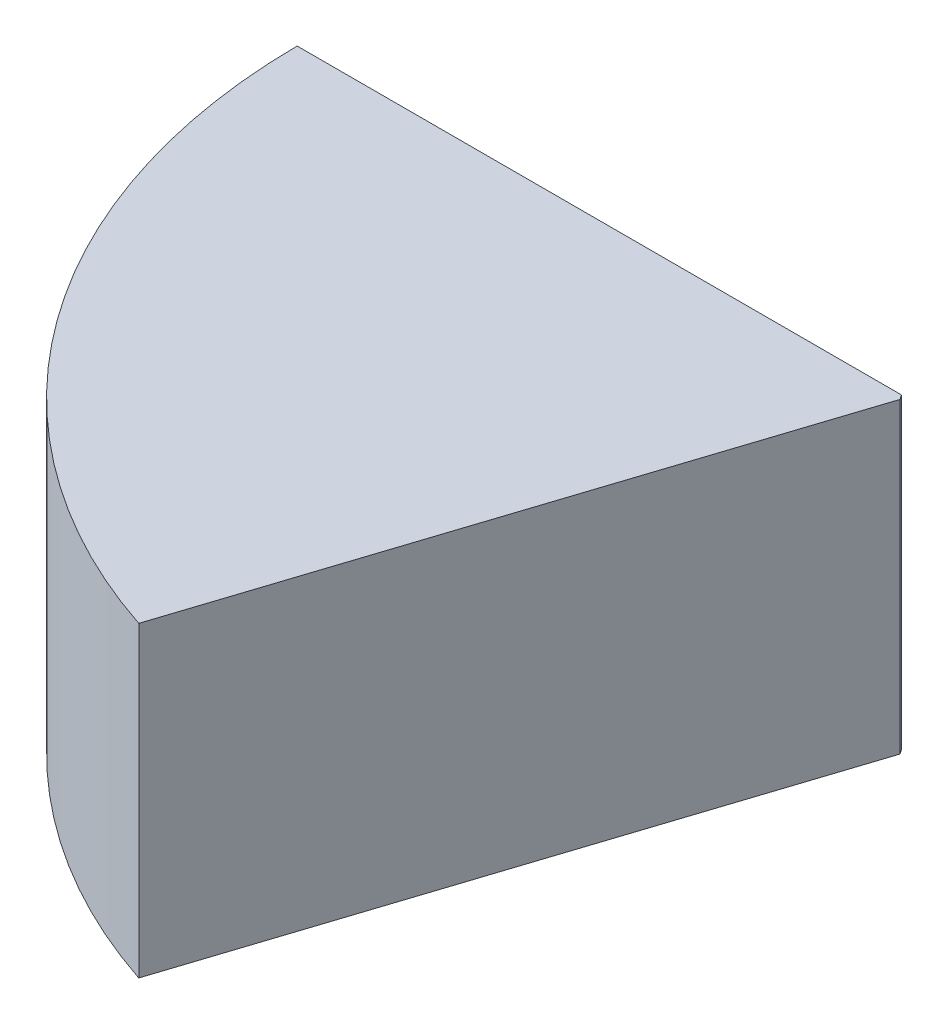
SolidWorks part; units mm, degrees
ref_plane "Front Plane" through (0, 0, 0) normal (0, 0, 1) x (1, 0, 0)
ref_plane "Top Plane" through (0, 0, 0) normal (0, 1, 0) x (1, 0, 0)
ref_plane "Right Plane" through (0, 0, 0) normal (1, 0, 0) x (0, 0, -1)
sketch "Sketch1" plane through (0, 0, 0) normal (0, 0, 1) x (1, 0, 0)
  line L0 (0, 0) -> (0, 50.8)
  line L1 (0, 50.8) -> (-101.6, 50.8)
  line L2 (-101.6, 50.8) -> (-101.6, 0)
  line L3 (-101.6, 0) -> (0, 0)
  dimension "D1" = 101.6
  dimension "D2" = 50.8
revolve "Revolve1" add sketch "Sketch1" angle 72 about L0
sketch "Sketch2" plane through (0, 0, 0) normal (0.9511, 0, 0.309) x (0.309, 0, -0.9511)
  line L4 (-101.6, 0) -> (0, 0)
  line L5 (0, 0) -> (0, 50.8)
  line L6 (0, 50.8) -> (-101.6, 50.8)
  line L7 (-101.6, 50.8) -> (-101.6, 0)
  line L8 (-101.6, 0) -> (0, 0)
  line L9 (0, 0) -> (0, 50.8)
  line L10 (0, 50.8) -> (-101.6, 50.8)
  line L11 (-101.6, 50.8) -> (-101.6, 0)
  dimension "D1" = 0
extrude "Cut-Extrude1" cut sketch "Sketch2" against normal blind 0.635
sketch "Sketch3" plane through (0, 0, 0) normal (0, 0, -1) x (-1, 0, 0)
  line L4 (0.6677, 50.8) -> (0.6677, 0)
  line L5 (0.6677, 0) -> (101.6, 0)
  line L6 (101.6, 0) -> (101.6, 50.8)
  line L7 (101.6, 50.8) -> (0.6677, 50.8)
  line L8 (0.6677, 50.8) -> (0.6677, 0)
  line L9 (0.6677, 0) -> (101.6, 0)
  line L10 (101.6, 0) -> (101.6, 50.8)
  line L11 (101.6, 50.8) -> (0.6677, 50.8)
  dimension "D1" = 0
extrude "Cut-Extrude2" cut sketch "Sketch3" against normal blind 0.635
sketch "Sketch4" plane through (0, 50.8, 0) normal (0, 1, 0) x (1, 0, 0)
  line L0 (-1.1166, -1.3815) -> (-1.6589, -0.635)
  line L1 (-0.874, -0.635) -> (-31.9994, -96.4292) construction
  line L2 (-101.598, -0.635) -> (-0.874, -0.635) construction
  line L3 (-1.6589, -0.635) -> (-0.874, -0.635)
  line L4 (-0.874, -0.635) -> (-1.1166, -1.3815)
  dimension "D1" = 0.635
extrude "Cut-Extrude3" cut sketch "Sketch4" against normal up to next
